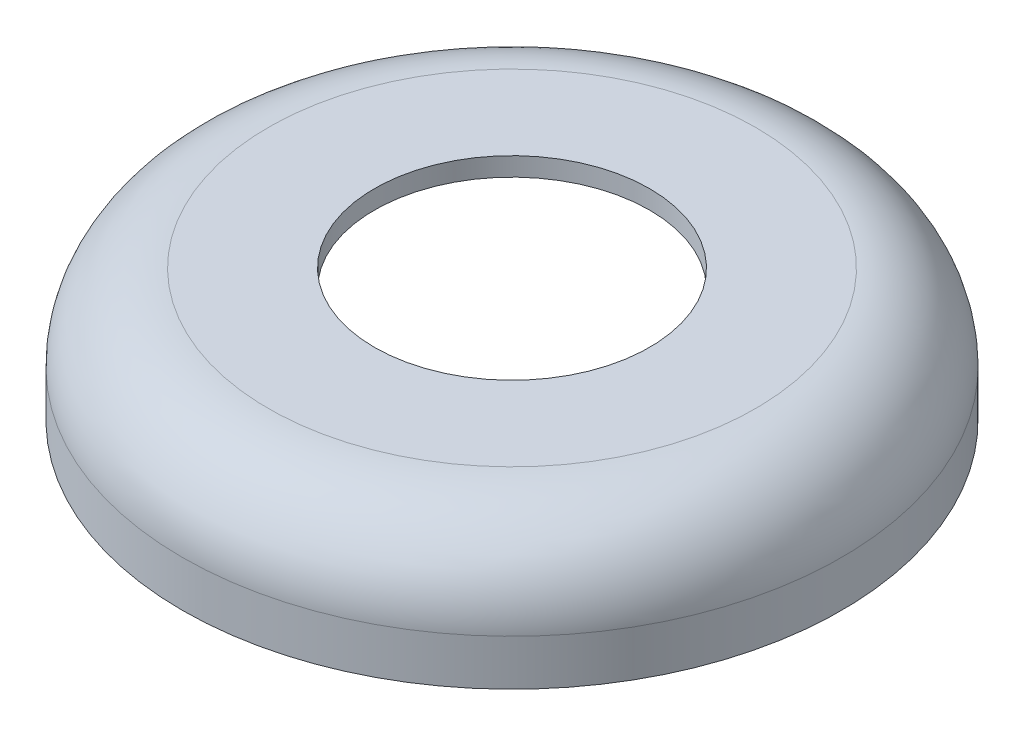
SolidWorks part; units mm, degrees
ref_plane "Front Plane" through (0, 0, 0) normal (0, 0, 1) x (1, 0, 0)
ref_plane "Top Plane" through (0, 0, 0) normal (0, 1, 0) x (1, 0, 0)
ref_plane "Right Plane" through (0, 0, 0) normal (1, 0, 0) x (0, 0, -1)
sketch "Sketch1" plane through (0, 0, 0) normal (0, 0, 1) x (1, 0, 0)
  line L1 (0, 0) -> (11.5, 0)
  line L2 (0, 0) -> (0, 4.6)
  line L3 (0, 4.6) -> (8.5, 4.6)
  line L4 (11.5, 0) -> (11.5, 1.6)
  arc A0 (8.5, 4.6) -> (11.5, 1.6) centre (8.5, 1.6) cw
  point P7 (11.5, 4.6)
  dimension "D3" = 3
  dimension "D1" = 4.6
  dimension "D2" = 11.5
revolve "Revolve1" add sketch "Sketch1" angle 360 about L2
shell "Shell1" thickness 0.65
sketch "Sketch2" plane through (0, 4.6, 0) normal (0, 1, 0) x (1, 0, 0)
  circle A0 centre (0, 0) radius 4.8
  dimension "D1" = 9.6
extrude "Cut-Extrude1" cut sketch "Sketch2" against normal blind 10
